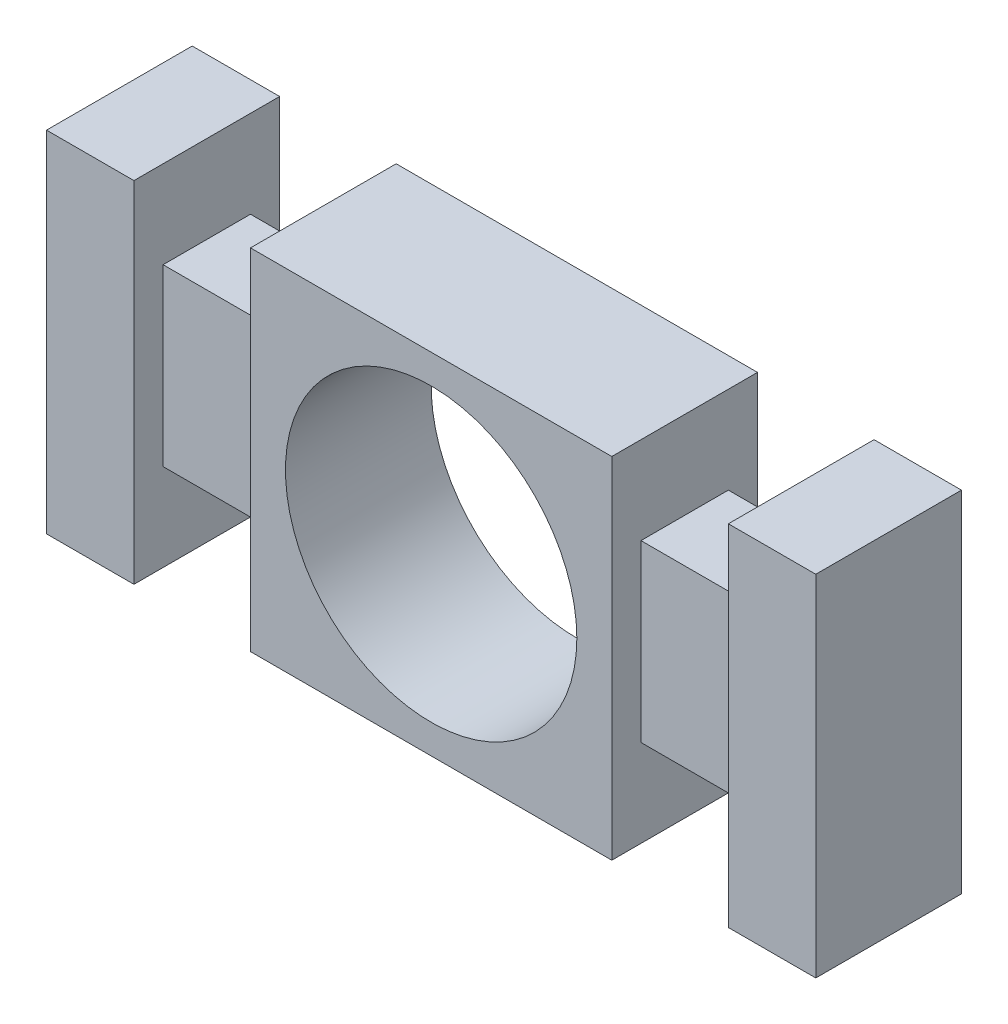
SolidWorks part; units mm, degrees
material "1023 Carbon Steel Sheet (SS)"
ref_plane "Front Plane" through (0, 0, 0) normal (1, 0, 0) x (0, 1, 0)
ref_plane "Top Plane" through (0, 0, 0) normal (0, 0, 1) x (0, 1, 0)
ref_plane "Right Plane" through (0, 0, 0) normal (0, 1, 0) x (-1, 0, 0)
sketch "Sketch1" plane through (0, 0, 0) normal (0, 0, 1) x (0, 1, 0)
  line L1 (-30, 66) -> (30, 66)
  line L2 (-30, 66) -> (-30, -66)
  line L3 (-30, -66) -> (30, -66)
  line L4 (30, 66) -> (30, -66)
  point P4 (0, 66)
  point P6 (0, -66)
  point P7 (30, 0)
  point P8 (-30, 0)
  dimension "D1" = 132
  dimension "D2" = 60
extrude "Boss-Extrude1" add sketch "Sketch1" along normal blind 25
sketch "Sketch2" plane through (0, 0, 25) normal (0, 0, 1) x (1, 0, 0)
  line L0 (-51, 30) -> (-51, 15)
  line L1 (66, 30) -> (-66, 30) construction
  line L2 (-51, 15) -> (-31, 15)
  line L3 (-31, 15) -> (-31, 30)
  line L4 (-31, 30) -> (-51, 30)
  line L5 (-66, 30) -> (-66, -30) construction
  line L6 (0, 0) -> (0, 30) construction
  line L7 (-66, 0) -> (66, 0) construction
  line L8 (66, -30) -> (66, 30) construction
  line L9 (31, 15) -> (31, 30)
  line L10 (51, 15) -> (31, 15)
  line L11 (51, 30) -> (51, 15)
  line L12 (31, 30) -> (51, 30)
  line L13 (51, -15) -> (31, -15)
  line L14 (51, -30) -> (51, -15)
  line L15 (31, -30) -> (51, -30)
  line L16 (31, -15) -> (31, -30)
  line L17 (-31, -15) -> (-31, -30)
  line L18 (-51, -15) -> (-31, -15)
  line L19 (-51, -30) -> (-51, -15)
  line L20 (-31, -30) -> (-51, -30)
  dimension "D1" = 20
  dimension "D2" = 15
  dimension "D3" = 15
extrude "Cut-Extrude1" cut sketch "Sketch2" against normal through all
sketch "Sketch4" plane through (0, 0, 25) normal (0, 0, 1) x (1, 0, 0)
  line L1 (-51, 15) -> (-31, 15)
  line L2 (-51, 15) -> (-51, -15)
  line L3 (-51, -15) -> (-31, -15)
  line L4 (-31, 15) -> (-31, -15)
  line L5 (51, 15) -> (31, 15)
  line L6 (51, 15) -> (51, -15)
  line L7 (51, -15) -> (31, -15)
  line L8 (31, 15) -> (31, -15)
extrude "Cut-Extrude2" cut sketch "Sketch4" against normal blind 5
sketch "Sketch5" plane through (0, 0, 0) normal (0, 0, -1) x (1, 0, 0)
  line L1 (-51, 15) -> (-31, 15)
  line L2 (-51, 15) -> (-51, -15)
  line L3 (-51, -15) -> (-31, -15)
  line L4 (-31, 15) -> (-31, -15)
  line L5 (51, 15) -> (31, 15)
  line L6 (51, 15) -> (51, -15)
  line L7 (51, -15) -> (31, -15)
  line L8 (31, 15) -> (31, -15)
extrude "Cut-Extrude3" cut sketch "Sketch5" against normal blind 5
sketch "Sketch6" plane through (0, 0, 25) normal (0, 0, 1) x (1, 0, 0)
  circle A0 centre (0, 0) radius 25
  dimension "D1" = 50
extrude "Cut-Extrude4" cut sketch "Sketch6" against normal through all
